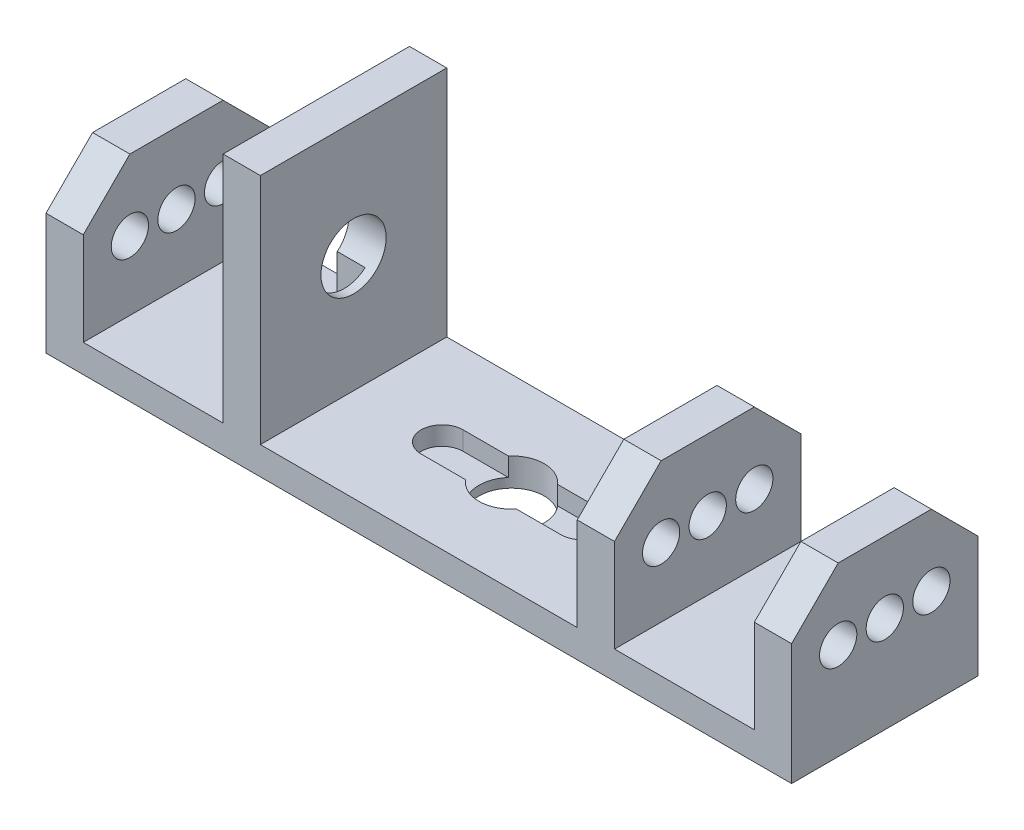
SolidWorks part; units mm, degrees
ref_plane "前视基准面" through (0, 0, 0) normal (0, 0, 1) x (1, 0, 0)
ref_plane "上视基准面" through (0, 0, 0) normal (0, 1, 0) x (1, 0, 0)
ref_plane "右视基准面" through (0, 0, 0) normal (1, 0, 0) x (0, 0, -1)
sketch "草图1" plane through (0, 0, 0) normal (0, 1, 0) x (1, 0, 0)
  line L1 (0, 0) -> (80, 0)
  line L2 (0, 0) -> (0, -20)
  line L3 (0, -20) -> (80, -20)
  line L4 (80, 0) -> (80, -20)
  dimension "D1" = 80
  dimension "D2" = 20
extrude "凸台-拉伸1" add sketch "草图1" along normal blind 3
sketch "草图2" plane through (0, 3, 0) normal (0, 1, 0) x (1, 0, 0)
  line L0 (0, 0) -> (0, -20) construction
  circle A0 centre (40, -10.0455) radius 3.5
  dimension "D1" = 7
  dimension "D2" = 40
extrude "切除-拉伸1" cut sketch "草图2" against normal blind 3
sketch "草图3" plane through (0, 3, 0) normal (0, 1, 0) x (1, 0, 0)
  line L0 (80, 0) -> (0, 0) construction
  line L1 (32.5, -7.75) -> (47.5, -7.75)
  line L2 (32.5, -7.75) -> (32.5, -12.25)
  line L3 (32.5, -12.25) -> (47.5, -12.25)
  line L4 (47.5, -7.75) -> (47.5, -12.25)
  circle A0 centre (40, -10.0455) radius 3.5 construction
  dimension "D1" = 4.5
  dimension "D2" = 7.75
  dimension "D3" = 15
  dimension "D4" = 7.5
extrude "切除-拉伸2" cut sketch "草图3" against normal blind 2
sketch "草图5" plane through (0, 3, 0) normal (0, 1, 0) x (1, 0, 0)
  line L0 (32.5, -7.75) -> (32.5, -12.25) construction
  line L1 (47.5, -12.25) -> (47.5, -7.75) construction
  circle A0 centre (32.5, -10) radius 2.25
  circle A1 centre (47.5, -10) radius 2.25
  dimension "D1" = 4.5
extrude "切除-拉伸3" cut sketch "草图5" against normal blind 2
sketch "草图6" plane through (0, 3, 0) normal (0, 1, 0) x (1, 0, 0)
  line L0 (0, -20) -> (80, -20) construction
  line L1 (0, 0) -> (4, 0)
  line L2 (0, 0) -> (0, -20)
  line L3 (0, -20) -> (4, -20)
  line L4 (4, 0) -> (4, -20)
  line L5 (80, 0) -> (0, 0) construction
  line L6 (80, 0) -> (76, 0)
  line L7 (80, 0) -> (80, -20)
  line L8 (80, -20) -> (76, -20)
  line L9 (76, 0) -> (76, -20)
  line L15 (57, 0) -> (61, 0)
  line L16 (57, 0) -> (57, -20)
  line L17 (57, -20) -> (61, -20)
  line L18 (61, 0) -> (61, -20)
  dimension "D1" = 4
  dimension "D2" = 4
  dimension "D4" = 4
  dimension "D6" = 15
extrude "凸台-拉伸2" add sketch "草图6" along normal blind 15
sketch "草图7" plane through (80, 0, 0) normal (1, 0, 0) x (0, 0, -1)
  line L0 (-20, 13) -> (-15, 18)
  line L1 (-20, 18) -> (-20, 0) construction
  line L2 (-20, 18) -> (0, 18) construction
  line L3 (-15, 18) -> (-20, 18)
  line L4 (-20, 18) -> (-20, 13)
  line L5 (0, 13) -> (0, 18)
  line L6 (0, 18) -> (0, 0) construction
  line L7 (0, 18) -> (-5, 18)
  line L8 (-5, 18) -> (0, 13)
  dimension "D1" = 5
extrude "切除-拉伸4" cut sketch "草图7" against normal blind 83
sketch "草图8" plane through (0, 0, 0) normal (-1, 0, 0) x (0, 0, 1)
  line L0 (5, 10.3869) -> (0, 10.3869) construction
  line L1 (0, 13) -> (0, 0) construction
  line L2 (5, 10.3869) -> (10, 10.3869) construction
  line L3 (10, 10.3869) -> (15, 10.3869) construction
  line L4 (15, 10.3869) -> (20, 10.3869) construction
  line L5 (20, 13) -> (20, 0) construction
  circle A0 centre (5, 10.3869) radius 2
  circle A1 centre (10, 10.3869) radius 2
  circle A2 centre (15, 10.3869) radius 2
extrude "切除-拉伸5" cut sketch "草图8" against normal blind 83
sketch "草图9" plane through (0, 3, 0) normal (0, 1, 0) x (1, 0, 0)
  line L1 (57, 0) -> (4, 0) construction
  line L2 (19, 0) -> (23, 0)
  line L3 (19, 0) -> (19, -20)
  line L4 (19, -20) -> (23, -20)
  line L6 (23, 0) -> (23, -20)
  line L7 (4, -20) -> (57, -20) construction
  line L8 (4, -20) -> (4, 0) construction
  point P10 (4, -10)
  dimension "D1" = 4
  dimension "D2" = 15
extrude "凸台-拉伸3" add sketch "草图9" along normal blind 25
sketch "草图10" plane through (19, 0, 0) normal (-1, 0, 0) x (0, 0, 1)
  line L1 (0, 28) -> (20, 28) construction
  line L2 (0, 28) -> (0, 3) construction
  circle A0 centre (10, 15.5) radius 3.5
  dimension "D1" = 7
  dimension "D2" = 12.5
  dimension "D3" = 10
extrude "切除-拉伸6" cut sketch "草图10" against normal blind 6
sketch "草图11" plane through (19, 0, 0) normal (-1, 0, 0) x (0, 0, 1)
  line L0 (0, 28) -> (20, 28) construction
  line L1 (7.75, 7.9) -> (12.25, 7.9)
  line L2 (7.75, 7.9) -> (7.75, 22.9)
  line L3 (7.75, 22.9) -> (12.25, 22.9)
  line L4 (12.25, 7.9) -> (12.25, 22.9)
  line L6 (0, 28) -> (0, 3) construction
  dimension "D1" = 15
  dimension "D2" = 4.5
  dimension "D3" = 5.1
  dimension "D4" = 7.75
extrude "切除-拉伸7" cut sketch "草图11" against normal blind 3
sketch "草图12" plane through (19, 0, 0) normal (-1, 0, 0) x (0, 0, 1)
  line L0 (12.25, 22.9) -> (7.75, 22.9) construction
  line L1 (7.75, 7.9) -> (12.25, 7.9) construction
  circle A0 centre (10, 22.9) radius 2.25
  circle A1 centre (10, 7.9) radius 2.25
  dimension "D1" = 4.5
extrude "切除-拉伸8" cut sketch "草图12" against normal blind 3
